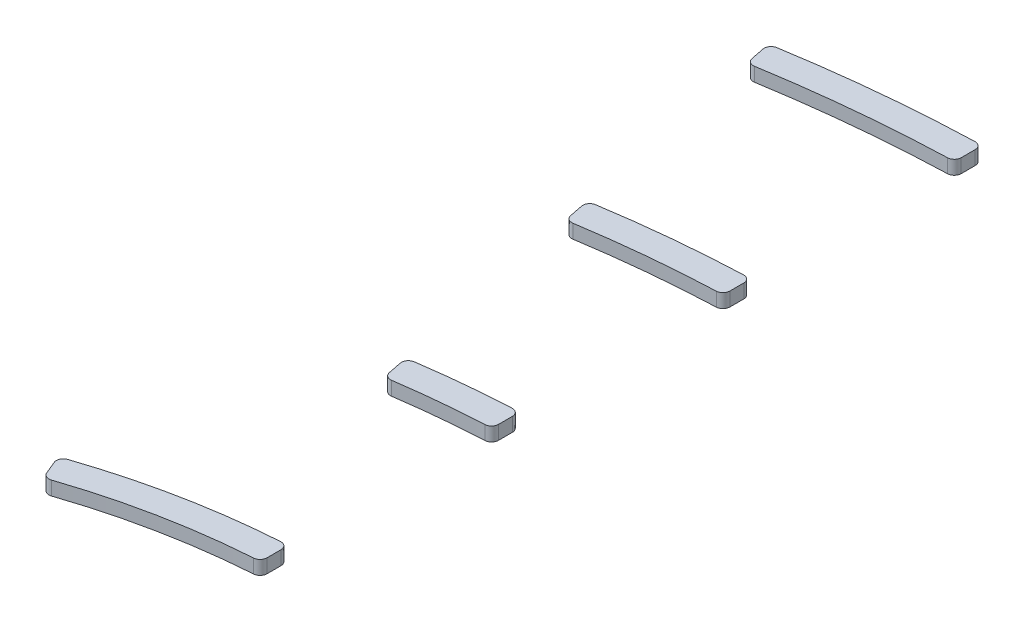
SolidWorks part; units mm, degrees
ref_plane "Ebene vorne" through (0, 0, 0) normal (0, 0, 1) x (1, 0, 0)
ref_plane "Ebene oben" through (0, 0, 0) normal (0, 1, 0) x (1, 0, 0)
ref_plane "Ebene rechts" through (0, 0, 0) normal (1, 0, 0) x (0, 0, -1)
sketch "Skizze1" plane through (0, 0, 0) normal (0, 1, 0) x (1, 0, 0)
  line L0 (-8.4593, 300.1656) -> (-8.4618, 297.1638)
  line L1 (-48.347, 139.1591) -> (-49.5, 141.9363)
  line L2 (-30.0556, 194.9982) -> (-30.6447, 197.9439)
  line L3 (-39.8657, 244.0563) -> (-40.4544, 247.0005)
  line L4 (-8.5428, 200.1201) -> (-8.5453, 197.1162)
  line L5 (-8.501, 250.1474) -> (-8.5035, 247.1449)
  line L6 (-49.6737, 293.1046) -> (-50.2624, 296.0481)
  line L7 (-8.5846, 150.0749) -> (-8.5871, 147.0678)
  arc A1 (-10.009, 301.666) -> (-49.0352, 297.8223) centre (0, 0) ccw
  arc A2 (-9.9115, 295.6659) -> (-47.9597, 291.9185) centre (0, 0) ccw
  arc A3 (-10.061, 251.6474) -> (-39.2171, 248.7763) centre (0, 0) ccw
  arc A4 (-9.9429, 245.6473) -> (-38.1619, 242.8686) centre (0, 0) ccw
  arc A5 (-10.118, 201.6195) -> (-29.3922, 199.7221) centre (0, 0) ccw
  arc A6 (-9.969, 195.6194) -> (-28.3675, 193.8082) centre (0, 0) ccw
  arc A7 (-10.1852, 151.5728) -> (-48.5945, 143.9327) centre (0, 0) ccw
  arc A8 (-9.9845, 145.5726) -> (-46.4838, 138.3124) centre (0, 0) ccw
  arc A9 (-9.9115, 295.6659) -> (-8.4618, 297.1638) centre (-9.9618, 297.1651) ccw
  arc A10 (-8.4593, 300.1656) -> (-10.009, 301.666) centre (-9.9593, 300.1668) ccw
  arc A11 (-50.2624, 296.0481) -> (-49.0352, 297.8223) centre (-48.7915, 296.3422) cw
  arc A12 (-47.9597, 291.9185) -> (-49.6737, 293.1046) centre (-48.2029, 293.3987) cw
  arc A13 (-9.9429, 245.6473) -> (-8.5035, 247.1449) centre (-10.0035, 247.1461) ccw
  arc A14 (-10.061, 251.6474) -> (-8.501, 250.1474) centre (-10.001, 250.1486) cw
  arc A15 (-39.2171, 248.7763) -> (-40.4544, 247.0005) centre (-38.9835, 247.2946) ccw
  arc A16 (-38.1619, 242.8686) -> (-39.8657, 244.0563) centre (-38.3948, 244.3504) cw
  arc A17 (-9.969, 195.6194) -> (-8.5453, 197.1162) centre (-10.0453, 197.1174) ccw
  arc A18 (-10.118, 201.6195) -> (-8.5428, 200.1201) centre (-10.0428, 200.1214) cw
  arc A19 (-29.3922, 199.7221) -> (-30.6447, 197.9439) centre (-29.1738, 198.238) ccw
  arc A20 (-30.0556, 194.9982) -> (-28.3675, 193.8082) centre (-28.5848, 195.2924) ccw
  arc A21 (-10.1852, 151.5728) -> (-8.5846, 150.0749) centre (-10.0846, 150.0762) cw
  arc A22 (-8.5871, 147.0678) -> (-9.9845, 145.5726) centre (-10.0871, 147.0691) cw
  arc A23 (-48.5945, 143.9327) -> (-49.5, 141.9363) centre (-48.1147, 142.5115) ccw
  arc A24 (-48.347, 139.1591) -> (-46.4838, 138.3124) centre (-46.9616, 139.7343) ccw
  point P35 (-8.458, 301.7135)
  point P38 (-50.5659, 297.5662)
  point P41 (-49.3889, 291.6801)
  point P46 (-8.4997, 251.705)
  point P49 (-40.7599, 248.5282)
  point P52 (-39.5827, 242.6411)
  point P55 (-8.5465, 195.6867)
  point P58 (-8.5415, 201.6925)
  point P63 (-29.7754, 193.5969)
  point P66 (-8.5833, 151.6719)
  point P69 (-8.5883, 145.6616)
  point P74 (-47.8078, 137.8604)
  dimension "D1" = 1.5
extrude "Aufsatz-Linear austragen1" add sketch "Skizze1" along normal blind 3
